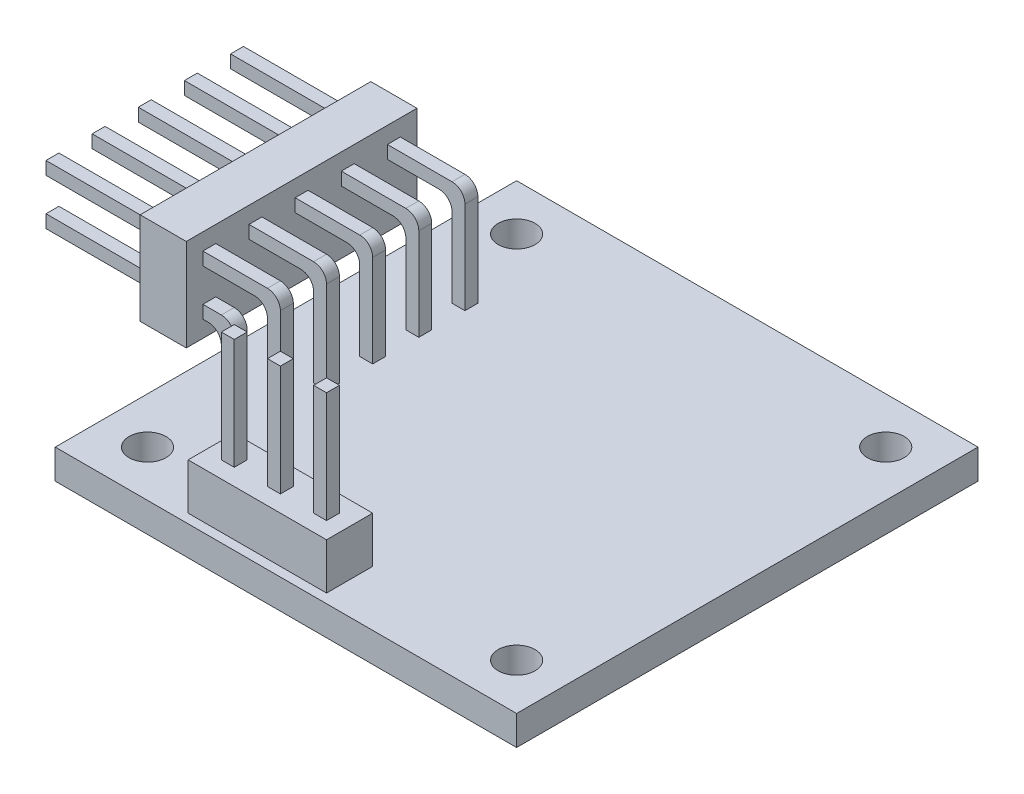
SolidWorks part; units mm, degrees
ref_plane "Front Plane" through (0, 0, 0) normal (0, 0, 1) x (1, 0, 0)
ref_plane "Top Plane" through (0, 0, 0) normal (0, 1, 0) x (1, 0, 0)
ref_plane "Right Plane" through (0, 0, 0) normal (1, 0, 0) x (0, 0, -1)
sketch "Sketch1" plane through (0, 0, 0) normal (0, 1, 0) x (1, 0, 0)
  line L1 (0, 0) -> (25, 0)
  line L2 (0, 0) -> (0, 25)
  line L3 (0, 25) -> (25, 25)
  line L4 (25, 0) -> (25, 25)
  line L5 (2.5, 22.5) -> (22.5, 22.5) construction
  line L6 (2.5, 22.5) -> (2.5, 2.5) construction
  line L7 (2.5, 2.5) -> (22.5, 2.5) construction
  line L8 (22.5, 22.5) -> (22.5, 2.5) construction
  circle A0 centre (2.5, 22.5) radius 1
  circle A1 centre (22.5, 22.5) radius 1
  circle A2 centre (22.5, 2.5) radius 1
  circle A3 centre (2.5, 2.5) radius 1
  dimension "D7" = 2
  dimension "D1" = 25
  dimension "D2" = 25
  dimension "D3" = 2.5
  dimension "D4" = 2.5
  dimension "D5" = 2.5
  dimension "D6" = 20
extrude "Boss-Extrude1" add sketch "Sketch1" along normal blind 1.6
sketch "Sketch3" plane through (0, 0, 0) normal (0, 0, 1) x (1, 0, 0)
  line L0 (1.5, 1.6) -> (1.5, 3.4)
  line L1 (0, 1.6) -> (25, 1.6) construction
  line L2 (0.8, 4.1) -> (-8, 4.1)
  line L3 (-8, 4.1) -> (-8, 4.8)
  line L4 (-8, 4.8) -> (1.5, 4.8)
  line L5 (2.2, 4.1) -> (2.2, 1.6)
  line L6 (2.2, 1.6) -> (1.5, 1.6)
  line L7 (4, 1.6) -> (4.7, 1.6)
  line L8 (4.7, 1.6) -> (4.7, 6.6)
  line L9 (4, 7.3) -> (-8, 7.3)
  line L10 (-8, 7.3) -> (-8, 6.6)
  line L11 (-8, 6.6) -> (3.3, 6.6)
  line L12 (4, 5.9) -> (4, 1.6)
  line L13 (0, 1.6) -> (0, 0) construction
  arc A0 (4.7, 6.6) -> (4, 7.3) centre (4, 6.6) ccw
  arc A1 (3.3, 6.6) -> (4, 5.9) centre (3.3, 5.9) cw
  arc A2 (1.5, 4.8) -> (2.2, 4.1) centre (1.5, 4.1) cw
  arc A3 (1.5, 3.4) -> (0.8, 4.1) centre (0.8, 3.4) ccw
  dimension "D5" = 0.7
  dimension "D1" = 0.7
  dimension "D2" = 0.7
  dimension "D3" = 0.7
  dimension "D4" = 0.7
  dimension "D6" = 2.5
  dimension "D7" = 1.5
  dimension "D8" = 8
  dimension "D9" = 2.5
  dimension "D10" = 2.5
extrude "Boss-Extrude2" add sketch "Sketch3" against normal blind 0.7 from offset 7.5 offset against normal yes
pattern_linear "LPattern1" count 5 spacing 2.5 along (0, 0, -1) of "Boss-Extrude2"
sketch "Sketch4" plane through (0, 0, -7.5) normal (0, 0, 1) x (1, 0, 0)
  line L0 (4, 7.3) -> (-8, 7.3) construction
  line L1 (-2, 8.2) -> (0.5, 8.2)
  line L2 (-2, 8.2) -> (-2, 3.2)
  line L3 (-2, 3.2) -> (0.5, 3.2)
  line L4 (0.5, 8.2) -> (0.5, 3.2)
  line L5 (-8, 4.1) -> (0.8, 4.1) construction
  line L7 (-8, 4.8) -> (-8, 4.1) construction
  dimension "D1" = 2.5
  dimension "D2" = 5
  dimension "D3" = 0.9
  dimension "D4" = 0.9
  dimension "D5" = 6
extrude "Boss-Extrude3" add sketch "Sketch4" against normal blind 11.6 and the other way blind 0.9
sketch "Sketch5" plane through (0, 1.6, 0) normal (0, 1, 0) x (1, 0, 0)
  line L0 (0, 0) -> (25, 0) construction
  line L1 (6.7, 3) -> (9.2, 3)
  line L2 (6.7, 3) -> (6.7, 0.5)
  line L3 (6.7, 0.5) -> (9.2, 0.5)
  line L4 (9.2, 3) -> (9.2, 0.5)
  line L5 (0, 25) -> (0, 0) construction
  dimension "D1" = 2.5
  dimension "D2" = 2.5
  dimension "D3" = 0.5
  dimension "D4" = 6.7
extrude "Boss-Extrude4" add sketch "Sketch5" along normal blind 2.5
sketch "Sketch6" plane through (0, 4.1, 0) normal (0, 1, 0) x (1, 0, 0)
  line L0 (6.7, 3) -> (9.2, 0.5) construction
  line L1 (7.6, 1.4) -> (8.3, 1.4)
  line L2 (7.6, 1.4) -> (7.6, 2.1)
  line L3 (7.6, 2.1) -> (8.3, 2.1)
  line L4 (8.3, 1.4) -> (8.3, 2.1)
  line L5 (7.6, 1.4) -> (8.3, 2.1) construction
  line L6 (7.6, 2.1) -> (8.3, 1.4) construction
  point P0 (7.95, 1.75)
  dimension "D1" = 0.7
  dimension "D2" = 0.7
extrude "Boss-Extrude5" add sketch "Sketch6" along normal blind 6
pattern_linear "LPattern2" count 3 spacing 2.5 along (1, 0, 0) of "Boss-Extrude5", "Boss-Extrude4"
equation "\"D4@Sketch1\"=\"D3@Sketch1\""
equation "\"D5@Sketch1\"=\"D3@Sketch1\""
